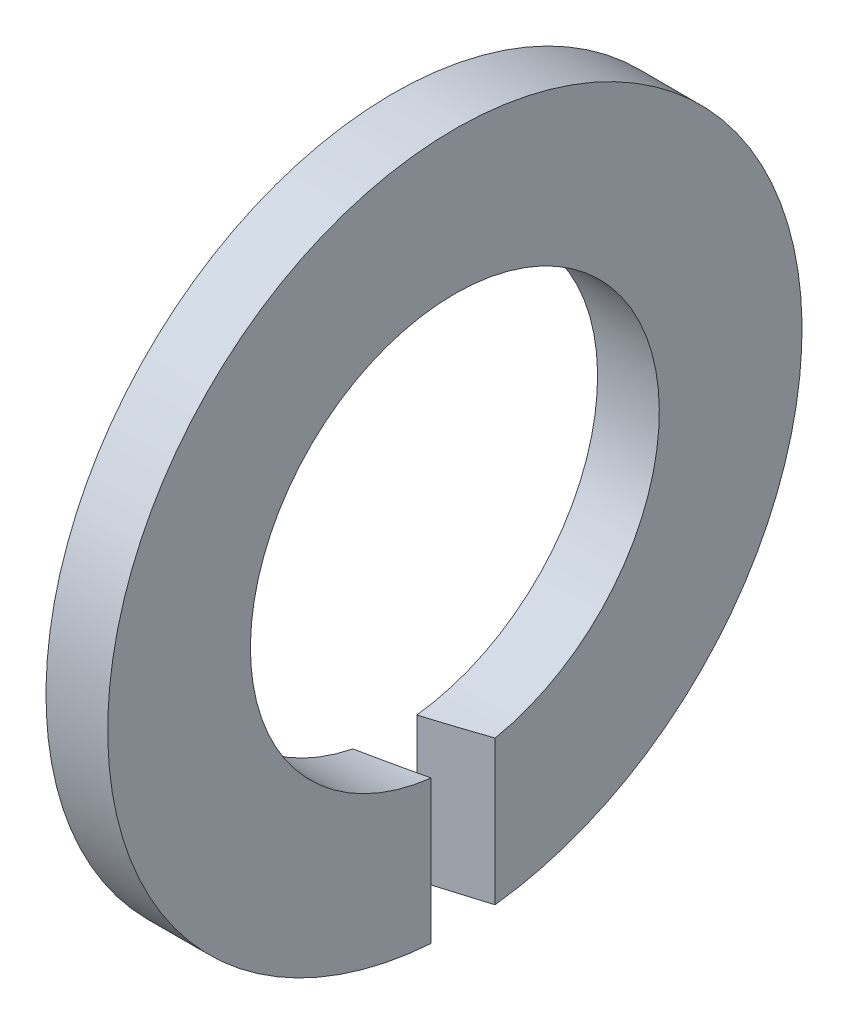
SolidWorks part; units mm, degrees
material "Acier non allié"
ref_plane "Plane1" through (0, 0, 0) normal (0, 0, 1) x (1, 0, 0)
ref_plane "Plane2" through (0, 0, 0) normal (0, 1, 0) x (1, 0, 0)
ref_plane "Plane3" through (0, 0, 0) normal (1, 0, 0) x (0, 0, -1)
sketch "Sketch1" plane through (0, 0, 0) normal (0, 0, 1) x (1, 0, 0)
  line L0 (-34.925, 0) -> (9.525, 0) construction
  line L1 (0, 2.65) -> (0, 4.5)
  line L2 (0, 4.5) -> (-0.8, 4.5)
  line L3 (-0.8, 4.5) -> (-0.8, 2.65)
  line L4 (-0.8, 2.65) -> (0, 2.65)
  dimension "Thickness" = 0.8
  dimension "Inside_dia" = 5.3
  dimension "Outside_dia" = 9
revolve "Base-Revolve" add sketch "Sketch1" angle 360 about L0
sketch "Esquisse1" plane through (0, 0, 0) normal (0, 1, 0) x (0, 0, -1)
  line L0 (-0.5213, 0.8) -> (-0.2515, -0.2071)
  line L1 (-0.5213, 0.8) -> (0.5213, 0) construction
  line L2 (0, 0) -> (0, 0.8) construction
  line L3 (-4.5, 0) -> (4.5, 0) construction
  line L4 (2.65, 0.8) -> (-2.65, 0.8) construction
  line L5 (-0.5213, 0.8) -> (0.2515, 1.0071)
  line L6 (0.2515, 1.0071) -> (0.5213, 0)
  line L7 (0.5213, 0) -> (-0.2515, -0.2071)
  point P0 (0, 0.4)
  dimension "D1" = 0.8
  dimension "D2" = 15
extrude "Enlèv. mat.-Extru.1" cut sketch "Esquisse1" against normal blind 10
